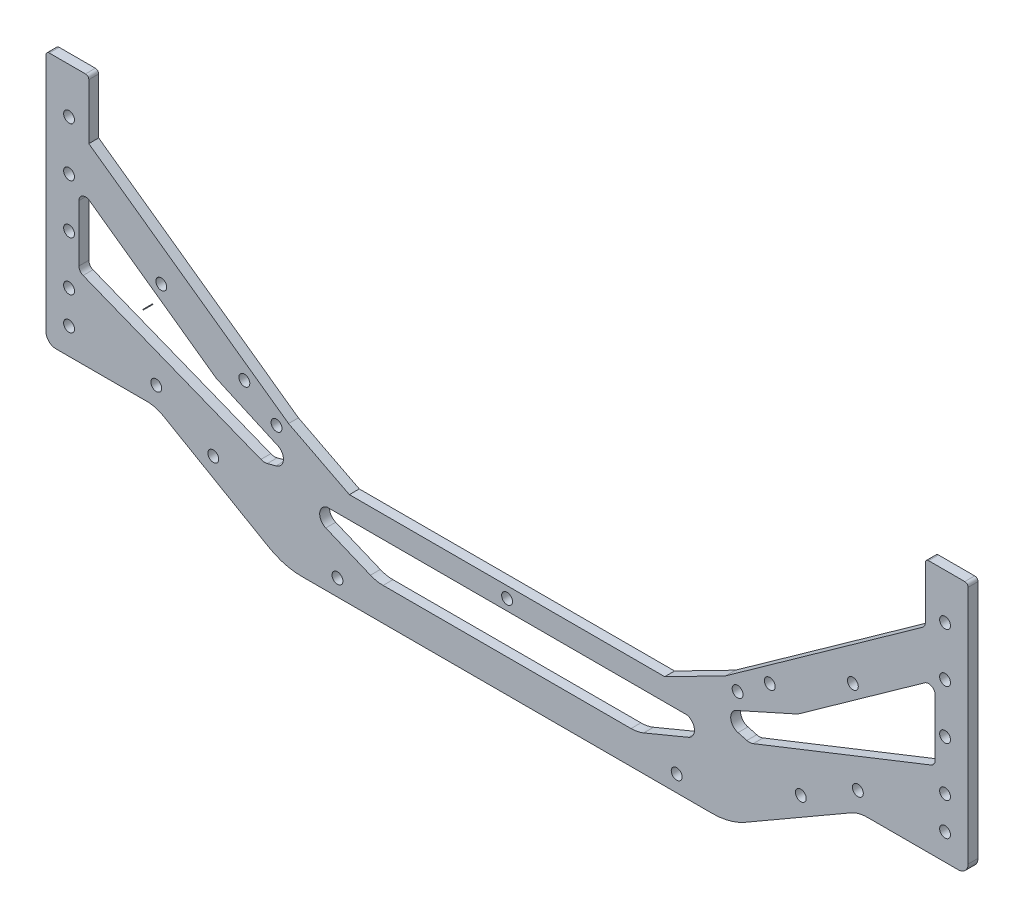
SolidWorks part; units mm, degrees
material "Thornel Mat VMA"
ref_plane "前视基准面" through (0, 0, 0) normal (0, 0, 1) x (1, 0, 0)
ref_plane "上视基准面" through (0, 0, 0) normal (0, 1, 0) x (1, 0, 0)
ref_plane "右视基准面" through (0, 0, 0) normal (1, 0, 0) x (0, 0, -1)
sketch "草图1" plane through (0, 0, 0) normal (0, 0, 1) x (1, 0, 0)
  line L0 (0, 0) -> (53, 0) construction
  line L1 (26.5, 0) -> (26.5, 36.4986) construction
  line L2 (91.5, 5) -> (-38.5, 5)
  line L3 (-38.5, 5) -> (-103.5, 42.5278)
  line L4 (-103.5, 42.5278) -> (-108.5, 33.8675)
  line L5 (-108.5, 33.8675) -> (-41.1795, -5)
  line L6 (-41.1795, -5) -> (94.1795, -5)
  line L7 (161.5, 33.8675) -> (94.1795, -5)
  line L8 (156.5, 42.5278) -> (161.5, 33.8675)
  line L9 (91.5, 5) -> (156.5, 42.5278)
  circle A0 centre (0, 0) radius 1.65
  circle A1 centre (53, 0) radius 1.65
  circle A2 centre (53, 0) radius 1.65
  point P17 (26.5, -5)
  point P20 (26.5, 5)
  dimension "D1" = 3.3
  dimension "D2" = 3.3
  dimension "D3" = 53
  dimension "D7" = 5
  dimension "D4" = 65
  dimension "D5" = 65
  dimension "D6" = 10
  dimension "D8" = 10
  dimension "D9" = 150
extrude "凸台-拉伸1" add sketch "草图1" along normal blind 3 contours L9 L2 L3 L4 L5 L6 L7 L8 A1 A0
fillet "圆角1" radius 20 4 edges at (94.1795, -5, 1.5) (91.5, 5, 1.5) (-41.1795, -5, 1.5) (-38.5, 5, 1.5)
sketch "草图2" plane through (0, 0, 3) normal (0, 0, 1) x (1, 0, 0)
  line L0 (-99.1343, 34.2337) -> (-40.4103, 0.3294) construction
  line L1 (-108.5, 33.8675) -> (-45.8205, -2.3205) construction
  line L2 (-43.141, 7.6795) -> (-103.5, 42.5278) construction
  line L3 (-103.5, 42.5278) -> (-108.5, 33.8675) construction
  line L4 (26.5, 5) -> (26.5, 36.9406) construction
  line L5 (86.141, 5) -> (-33.141, 5) construction
  circle A1 centre (-62.6987, 13.1976) radius 1.65
  circle A2 centre (-80.0192, 23.1976) radius 1.65
  circle A3 centre (133.0192, 23.1976) radius 1.65
  circle A4 centre (115.6987, 13.1976) radius 1.65
  circle A6 centre (-25, 0) radius 1.65
  circle A7 centre (0, 0) radius 1.65 construction
  circle A8 centre (78, 0) radius 1.65
  dimension "D2" = 3.3
  dimension "D3" = 3.3
  dimension "D4" = 3.3
  dimension "D5" = 30
  dimension "D6" = 20
  dimension "D7" = 25
  dimension "D1" = 5
extrude "切除-拉伸1" cut sketch "草图2" against normal blind 10
sketch "草图3" plane through (0, 0, 3) normal (0, 0, 1) x (1, 0, 0)
  line L0 (-103.5, 42.5278) -> (-13.141, 5)
  line L1 (-43.141, 7.6795) -> (-103.5, 42.5278) construction
  line L2 (86.141, 5) -> (-33.141, 5) construction
  line L3 (-13.141, 5) -> (-33.141, 5)
  line L4 (-43.141, 7.6795) -> (-103.5, 42.5278)
  line L5 (26.5, 5) -> (26.5, 26.1465) construction
  line L6 (156.5, 42.5278) -> (66.141, 5)
  line L7 (96.141, 7.6795) -> (156.5, 42.5278)
  line L8 (66.141, 5) -> (86.141, 5)
  arc A0 (-43.141, 7.6795) -> (-33.141, 5) centre (-33.141, 25) ccw construction
  arc A1 (-43.141, 7.6795) -> (-33.141, 5) centre (-33.141, 25) ccw
  arc A2 (96.141, 7.6795) -> (86.141, 5) centre (86.141, 25) cw
  dimension "D1" = 20
extrude "凸台-拉伸2" add sketch "草图3" against normal up to vertex (3 mm away)
fillet "圆角2" radius 10 2 edges at (66.141, 5, 1.5) (-13.141, 5, 1.5)
sketch "草图4" plane through (0, 0, 3) normal (0, 0, 1) x (1, 0, 0)
  line L0 (-103.5, 42.5278) -> (-108.5, 33.8675)
  line L1 (-108.5, 33.8675) -> (-80.1987, 17.5278)
  line L2 (-108.5, 33.8675) -> (-45.8205, -2.3205) construction
  line L3 (-80.1987, 17.5278) -> (-113.5, 17.5278)
  line L4 (-113.5, 17.5278) -> (-113.5, 42.5278)
  line L5 (-113.5, 42.5278) -> (-103.5, 42.5278)
  line L6 (26.5, 5) -> (26.5, 66.9816) construction
  line L7 (64.147, 5) -> (-11.147, 5) construction
  line L8 (166.5, 17.5278) -> (166.5, 42.5278)
  line L9 (133.1987, 17.5278) -> (166.5, 17.5278)
  line L10 (161.5, 33.8675) -> (133.1987, 17.5278)
  line L11 (156.5, 42.5278) -> (161.5, 33.8675)
  line L12 (166.5, 42.5278) -> (156.5, 42.5278)
  dimension "D1" = 25
  dimension "D2" = 10
extrude "凸台-拉伸3" add sketch "草图4" against normal up to surface (3 mm away) up to face at (26.5, 13.1653, 0)
fillet "圆角3" radius 10 2 edges at (133.1987, 17.5278, 1.5) (-80.1987, 17.5278, 1.5)
fillet "圆角4" radius 3 4 edges at (166.5, 42.5278, 1.5) (166.5, 17.5278, 1.5) (-113.5, 42.5278, 1.5) (-113.5, 17.5278, 1.5)
sketch "草图6" plane through (0, 0, 3) normal (0, 0, 1) x (1, 0, 0)
  line L0 (26.5, 5) -> (26.5, 46.6071) construction
  line L1 (64.147, 5) -> (-11.147, 5) construction
  line L2 (-103.5, 42.5278) -> (-110.5, 42.5278) construction
  line L3 (-113.5, 39.5278) -> (-113.5, 20.5278) construction
  circle A0 centre (-106.5, 35.5278) radius 1.65
  circle A1 centre (-106.5, 25.5278) radius 1.65
  circle A2 centre (159.5, 25.5278) radius 1.65
  circle A3 centre (159.5, 35.5278) radius 1.65
  dimension "D1" = 3.3
  dimension "D2" = 3.3
  dimension "D3" = 7
  dimension "D4" = 10
  dimension "D5" = 7
extrude "切除-拉伸2" cut sketch "草图6" against normal blind 5
sketch "草图7" plane through (0, 0, 3) normal (0, 0, 1) x (1, 0, 0)
  line L0 (-47.3074, 19.1899) -> (-13.5, 28.2486)
  line L1 (-14.9825, 5.7648) -> (-103.5, 42.5278) construction
  line L2 (-13.5, 28.2486) -> (26.5, 28.2486)
  line L3 (26.5, 5) -> (26.5, 100.835) construction
  line L4 (64.147, 5) -> (-11.147, 5) construction
  line L5 (-45.4957, 12.4285) -> (-12.5784, 21.2486)
  line L6 (-12.5784, 21.2486) -> (26.5, 21.2486)
  line L7 (-47.3074, 19.1899) -> (-45.4957, 12.4285)
  line L8 (65.5784, 21.2486) -> (26.5, 21.2486)
  line L9 (98.4957, 12.4285) -> (65.5784, 21.2486)
  line L10 (66.5, 28.2486) -> (26.5, 28.2486)
  line L11 (100.3074, 19.1899) -> (66.5, 28.2486)
  line L12 (100.3074, 19.1899) -> (98.4957, 12.4285)
  dimension "D1" = 165
  dimension "D2" = 35
  dimension "D3" = 40
  dimension "D4" = 7
extrude "凸台-拉伸4" add sketch "草图7" against normal up to surface (3 mm away) up to face at (161.15, 35.5278, 0)
sketch "草图8" plane through (0, 0, 3) normal (0, 0, 1) x (1, 0, 0)
  line L0 (26.5, 5) -> (26.5, 83.5373) construction
  line L1 (64.147, 5) -> (-11.147, 5) construction
  circle A0 centre (-106.5, 25.5278) radius 1.65 construction
  circle A1 centre (-106.5, 35.5278) radius 1.65 construction
  circle A2 centre (-106.5, 25.5278) radius 1.65
  circle A3 centre (-106.5, 35.5278) radius 1.65
  circle A4 centre (-98.5, 35.5278) radius 1.65
  circle A5 centre (-98.5, 25.5278) radius 1.65
  circle A6 centre (151.5, 25.5278) radius 1.65
  circle A7 centre (151.5, 35.5278) radius 1.65
  circle A8 centre (159.5, 35.5278) radius 1.65
  circle A9 centre (159.5, 25.5278) radius 1.65
  dimension "D1" = 2
extrude "切除-拉伸3" cut sketch "草图8" against normal blind 10
sketch "草图9" plane through (0, 0, 3) normal (0, 0, 1) x (1, 0, 0)
  line L0 (-13.5, 28.2486) -> (-110.9118, 54.35)
  line L1 (-110.9118, 54.35) -> (-113.5, 44.6908)
  line L2 (-113.5, 44.6908) -> (-32.8185, 23.0722)
  line L3 (-13.5, 28.2486) -> (-47.3074, 19.1899) construction
  line L4 (66.5, 28.2486) -> (-13.5, 28.2486) construction
  line L5 (-106.5, 35.5278) -> (-106.5, 52.0247) construction
  line L6 (-32.8185, 23.0722) -> (-13.5, 28.2486)
  line L7 (26.5, 28.2486) -> (26.5, 99.0808) construction
  line L8 (166.5, 44.6908) -> (85.8185, 23.0722)
  line L9 (163.9118, 54.35) -> (166.5, 44.6908)
  line L10 (66.5, 28.2486) -> (163.9118, 54.35)
  line L11 (85.8185, 23.0722) -> (66.5, 28.2486)
  line L12 (-113.5, 39.5278) -> (-113.5, 20.5278) construction
  dimension "D3" = 10
  dimension "D4" = 165
extrude "凸台-拉伸5" add sketch "草图9" against normal up to surface (3 mm away) up to face at (153.15, 25.5278, 0)
fillet "圆角5" radius 3 14 edges at (66.5, 28.2486, 1.5) (-13.5, 28.2486, 1.5) (-32.8185, 23.0722, 1.5) (-47.3074, 19.1899, 1.5) (-36.7011, 14.7849, 1.5) (-12.5784, 21.2486, 1.5) (65.5784, 21.2486, 1.5) (89.7011, 14.7849, 1.5) (100.3074, 19.1899, 1.5) (85.8185, 23.0722, 1.5) (166.5, 44.6908, 1.5) (163.9118, 54.35, 1.5) (-113.5, 44.6908, 1.5) (-110.9118, 54.35, 1.5)
sketch "草图10" plane through (0, 0, 3) normal (0, 0, 1) x (1, 0, 0)
  line L0 (174.5, 103.4145) -> (174.5, 73.4145) construction
  line L1 (-121.5, 103.4145) -> (-121.5, 73.4145) construction
  line L2 (-108.3577, 67.8631) -> (-113.5, 61.7348)
  line L3 (-113.5, 61.7348) -> (-101.7846, 51.9044)
  line L4 (-13.8815, 28.3508) -> (-108.014, 53.5736) construction
  line L5 (-101.7846, 51.9044) -> (-83.5, 47.005)
  line L6 (-83.5, 47.005) -> (-108.3577, 67.8631)
  line L7 (-113.5, 39.5278) -> (-113.5, 20.5278) construction
  line L8 (26.5, 28.2486) -> (26.5, 127.7041) construction
  line L9 (66.105, 28.2486) -> (-13.105, 28.2486) construction
  line L10 (136.5, 47.005) -> (161.3577, 67.8631)
  line L11 (154.7846, 51.9044) -> (136.5, 47.005)
  line L12 (166.5, 61.7348) -> (154.7846, 51.9044)
  line L13 (161.3577, 67.8631) -> (166.5, 61.7348)
  dimension "D3" = 8
  dimension "D4" = 155
  dimension "D5" = 38
extrude "凸台-拉伸6" add sketch "草图10" against normal up to vertex (3 mm away)
fillet "圆角6" radius 2 8 edges at (161.3577, 67.8631, 1.5) (166.5, 61.7348, 1.5) (154.7846, 51.9044, 1.5) (136.5, 47.005, 1.5) (-83.5, 47.005, 1.5) (-101.7846, 51.9044, 1.5) (-108.3577, 67.8631, 1.5) (-113.5, 61.7348, 1.5)
sketch "草图11" plane through (0, 0, 3) normal (0, 0, 1) x (1, 0, 0)
  line L0 (26.5, 28.2486) -> (26.5, 115.9487) construction
  line L1 (-113.5, 39.5278) -> (-103.5, 39.5278)
  line L2 (-113.5, 39.5278) -> (-113.5, 106.9145)
  line L3 (-113.5, 106.9145) -> (-103.5, 106.9145)
  line L4 (-103.5, 39.5278) -> (-103.5, 106.9145)
  line L5 (66.105, 28.2486) -> (-13.105, 28.2486) construction
  line L6 (156.5, 39.5278) -> (156.5, 106.9145)
  line L7 (166.5, 106.9145) -> (156.5, 106.9145)
  line L8 (166.5, 39.5278) -> (166.5, 106.9145)
  line L9 (166.5, 39.5278) -> (156.5, 39.5278)
  dimension "D2" = 10
extrude "凸台-拉伸7" add sketch "草图11" against normal up to surface (3 mm away) up to face at (108.924, 25.2185, 0)
sketch "草图14" plane through (0, 0, 3) normal (0, 0, 1) x (1, 0, 0)
  line L0 (166.5, 20.5278) -> (166.5, 106.9145) construction
  line L1 (-113.5, 106.9145) -> (166.5, 106.9145)
  line L2 (-113.5, 106.9145) -> (-113.5, 97.32)
  line L3 (-113.5, 97.32) -> (166.5, 97.32)
  line L4 (166.5, 106.9145) -> (166.5, 97.32)
extrude "切除-拉伸6" cut sketch "草图14" against normal blind 30
sketch "草图15" plane through (0, 0, 3) normal (0, 0, 1) x (1, 0, 0)
  line L0 (-48.2493, 19.5811) -> (-113.5, 45.4145)
  line L1 (-113.5, 45.4145) -> (-113.5, 58.9239)
  line L2 (-113.5, 58.9239) -> (-71.8142, 33.5211)
  line L3 (-99.9952, 41.0722) -> (-43.6332, 25.97) construction
  line L4 (-71.8142, 33.5211) -> (-43.6332, 25.97)
  line L5 (-113.5, 97.32) -> (-113.5, 20.5278) construction
  line L6 (-43.6332, 20.1744) -> (-46.3222, 19.4539)
  line L7 (26.5, 28.2486) -> (26.5, 82.7426) construction
  line L8 (66.105, 28.2486) -> (-13.105, 28.2486) construction
  line L9 (124.8142, 33.5211) -> (96.6332, 25.97)
  line L10 (166.5, 58.9239) -> (124.8142, 33.5211)
  line L11 (166.5, 45.4145) -> (166.5, 58.9239)
  line L12 (101.2493, 19.5811) -> (166.5, 45.4145)
  line L13 (96.6332, 20.1744) -> (99.3222, 19.4539)
  arc A0 (-48.2493, 19.5811) -> (-46.3222, 19.4539) centre (-47.0987, 22.3517) ccw construction
  arc A1 (-43.6332, 20.1744) -> (-43.6332, 25.97) centre (-44.4096, 23.0722) ccw construction
  arc A2 (-48.2493, 19.5811) -> (-46.3222, 19.4539) centre (-47.0987, 22.3517) ccw
  arc A3 (-43.6332, 20.1744) -> (-43.6332, 25.97) centre (-44.4096, 23.0722) ccw
  arc A4 (96.6332, 20.1744) -> (96.6332, 25.97) centre (97.4096, 23.0722) cw
  arc A5 (101.2493, 19.5811) -> (99.3222, 19.4539) centre (100.0987, 22.3517) cw
extrude "切除-拉伸7" cut sketch "草图15" against normal blind 10
sketch "草图16" plane through (0, 0, 3) normal (0, 0, 1) x (1, 0, 0)
  line L1 (-13.8815, 28.3508) -> (-83.0717, 46.8903) construction
  line L2 (-48.4766, 37.6206) -> (-84.0799, 40.9549)
  line L3 (-84.0799, 40.9549) -> (-103.5, 62.787)
  line L5 (136.0717, 46.8903) -> (66.8815, 28.3508) construction
  line L6 (101.4766, 37.6206) -> (136.7238, 40.9549)
  line L7 (136.7238, 40.9549) -> (156.5, 62.787)
  line L9 (-103.5, 62.787) -> (-103.5, 65.787)
  line L10 (-103.5, 63.787) -> (-103.5, 97.32) construction
  line L11 (-103.5, 65.787) -> (-48.4766, 37.6206)
  line L12 (101.4766, 37.6206) -> (156.5, 65.787)
  line L14 (156.5, 65.787) -> (156.5, 62.787)
  line L17 (156.5, 97.32) -> (156.5, 63.787) construction
  dimension "D1" = 3
  dimension "D2" = 1
  dimension "D3" = 3
  dimension "D4" = 1
extrude "凸台-拉伸12" add sketch "草图16" against normal up to vertex (3 mm away)
sketch "草图18" plane through (0, 0, 3) normal (0, 0, 1) x (1, 0, 0)
sketch "草图20" plane through (0, 0, 3) normal (0, 0, 1) x (1, 0, 0)
  line L6 (81.1777, 17.0688) -> (-28.1777, 17.0688)
  line L8 (-28.1777, 17.0688) -> (-12.1835, 24.1453)
  line L9 (-12.1835, 24.1453) -> (57.5138, 24.1453)
  line L10 (57.5138, 24.1453) -> (81.1777, 17.0688)
extrude "凸台-拉伸15" add sketch "草图20" against normal up to surface (3 mm away) up to face at (18.4088, 34.2671, 0)
sketch "草图21" plane through (0, 0, 0) normal (0, 0, -1) x (-1, 0, 0)
  line L0 (-101.4766, 37.6206) -> (-74.3777, 23.7486)
  line L1 (-74.3777, 23.7486) -> (21.3777, 23.7486)
  line L2 (21.3777, 23.7486) -> (46.901, 36.814)
  line L3 (48.4766, 37.6206) -> (103.5, 65.787) construction
  line L4 (-156.5, 65.787) -> (-101.4766, 37.6206) construction
  line L6 (13.105, 28.2486) -> (-66.105, 28.2486) construction
  line L7 (-101.4766, 37.6206) -> (46.901, 36.814)
  dimension "D1" = 4.5
extrude "切除-拉伸10" cut sketch "草图21" against normal blind 10
sketch "草图22" plane through (0, 0, 3) normal (0, 0, 1) x (1, 0, 0)
  line L0 (-113.5, 45.4145) -> (-48.2493, 19.5811) construction
  line L1 (-113.5, 58.9239) -> (-103.5, 58.9239)
  line L2 (-113.5, 58.9239) -> (-113.5, 41.4554)
  line L3 (-113.5, 41.4554) -> (-103.5, 41.4554)
  line L4 (-103.5, 58.9239) -> (-103.5, 41.4554)
  line L5 (101.2493, 19.5811) -> (166.5, 45.4145) construction
  line L6 (166.5, 58.9239) -> (156.5, 58.9239)
  line L7 (166.5, 58.9239) -> (166.5, 41.4554)
  line L8 (166.5, 41.4554) -> (156.5, 41.4554)
  line L9 (156.5, 58.9239) -> (156.5, 41.4554)
extrude "凸台-拉伸16" add sketch "草图22" against normal up to surface (3 mm away) up to face at (26.5, 9.7947, 0)
sketch "草图23" plane through (0, 0, 3) normal (0, 0, 1) x (1, 0, 0)
  line L0 (-103.5, 52.83) -> (-43.6332, 25.97)
  line L1 (-43.6332, 25.97) -> (-71.8142, 33.5211)
  line L2 (-71.8142, 33.5211) -> (-103.5, 52.83)
  line L3 (96.6332, 25.97) -> (156.5, 52.83)
  line L4 (156.5, 52.83) -> (124.8142, 33.5211)
  line L5 (124.8142, 33.5211) -> (96.6332, 25.97)
extrude "切除-拉伸11" cut sketch "草图23" against normal blind 10
sketch "草图24" plane through (0, 0, 3) normal (0, 0, 1) x (1, 0, 0)
  line L0 (-46.901, 36.814) -> (-54.0368, 40.4668)
  line L1 (-48.4766, 37.6206) -> (-103.5, 65.787) construction
  line L2 (-54.0368, 40.4668) -> (-39.643, 38.6404)
  line L3 (-39.643, 38.6404) -> (-44.3618, 35.5142)
  line L4 (-46.901, 36.814) -> (-21.3777, 23.7486) construction
  line L5 (-44.3618, 35.5142) -> (-46.901, 36.814)
extrude "切除-拉伸12" cut sketch "草图24" against normal blind 10
sketch "草图25" plane through (0, 0, 3) normal (0, 0, 1) x (1, 0, 0)
  line L1 (-113.5, 97.32) -> (166.5, 97.32)
  line L2 (-113.5, 97.32) -> (-113.5, 94.32)
  line L3 (-113.5, 94.32) -> (166.5, 94.32)
  line L4 (166.5, 97.32) -> (166.5, 94.32)
  line L5 (166.5, 20.5278) -> (166.5, 97.32) construction
  dimension "D1" = 3
  dimension "D2" = 280
extrude "切除-拉伸13" cut sketch "草图25" against normal blind 10
sketch "草图26" plane through (0, 0, 3) normal (0, 0, 1) x (1, 0, 0)
  line L1 (-103.5, 94.32) -> (-100.5, 94.32)
  line L2 (-103.5, 94.32) -> (-103.5, 59.32)
  line L3 (-103.5, 59.32) -> (-100.5, 59.32)
  line L4 (-100.5, 94.32) -> (-100.5, 59.32)
  line L5 (156.5, 94.32) -> (153.5, 94.32)
  line L6 (156.5, 94.32) -> (156.5, 59.32)
  line L7 (156.5, 59.32) -> (153.5, 59.32)
  line L8 (153.5, 94.32) -> (153.5, 59.32)
  dimension "D1" = 35
  dimension "D2" = 3
  dimension "D3" = 35
  dimension "D4" = 3
extrude "凸台-拉伸17" add sketch "草图26" against normal up to surface (3 mm away) up to face at (26.5, 34.1676, 0)
sketch "草图27" plane through (0, 0, 3) normal (0, 0, 1) x (1, 0, 0)
  line L0 (-106.5, 35.5278) -> (-106.5, 80.5278) construction
  line L1 (159.5, 35.5278) -> (159.5, 80.5278) construction
  circle A0 centre (-106.5, 65.5278) radius 1.65
  circle A1 centre (-106.5, 80.5278) radius 1.65
  circle A2 centre (-106.5, 35.5278) radius 1.65 construction
  circle A3 centre (159.5, 65.5278) radius 1.65
  circle A4 centre (159.5, 80.5278) radius 1.65
  circle A5 centre (159.5, 35.5278) radius 1.65 construction
  circle A6 centre (-106.5, 50.5278) radius 1.65
  circle A7 centre (159.5, 50.5278) radius 1.65
  dimension "D1" = 3.3
  dimension "D2" = 3.3
  dimension "D3" = 30
  dimension "D4" = 15
  dimension "D5" = 3.3
  dimension "D6" = 3.3
  dimension "D8" = 15
  dimension "D9" = 3.3
  dimension "D10" = 3.3
  dimension "D11" = 15
  dimension "D12" = 15
  dimension "D7" = 30
extrude "切除-拉伸14" cut sketch "草图27" against normal blind 10
fillet "圆角7" radius 1 4 edges at (166.5, 94.32, 1.5) (153.5, 94.32, 1.5) (-113.5, 94.32, 1.5) (-100.5, 94.32, 1.5)
sketch "草图28" plane through (0, 0, 3) normal (0, 0, 1) x (1, 0, 0)
  circle A0 centre (-98.5, 25.5278) radius 1.65 construction
  circle A1 centre (-98.5, 35.5278) radius 1.65 construction
  circle A2 centre (151.5, 25.5278) radius 1.65 construction
  circle A3 centre (151.5, 35.5278) radius 1.65 construction
  circle A4 centre (-98.5, 25.5278) radius 1.65
  circle A5 centre (-98.5, 35.5278) radius 1.65
  circle A6 centre (151.5, 25.5278) radius 1.65
  circle A7 centre (151.5, 35.5278) radius 1.65
extrude "凸台-拉伸18" add sketch "草图28" against normal up to surface (3 mm away) up to face at (-104.85, 50.5278, 0)
sketch "草图29" plane through (0, 0, 3) normal (0, 0, 1) x (1, 0, 0)
  line L0 (-100.5, 82.608) -> (-27.3401, 23.0168)
  line L1 (-100.5, 64.2513) -> (-100.5, 93.32) construction
  line L3 (-43.6332, 25.97) -> (-103.5, 52.83) construction
  line L4 (-43.6332, 25.97) -> (-100.5, 72.29)
  line L5 (-100.5, 82.608) -> (-100.5, 72.29)
  line L6 (-43.6332, 25.97) -> (-27.3401, 23.0168)
  dimension "D1" = 15
  dimension "D2" = 8
  dimension "D3" = 8
extrude "凸台-拉伸19" add sketch "草图29" against normal up to surface (3 mm away) up to face at (-104.85, 50.5278, 0)
sketch "草图30" plane through (0, 0, 3) normal (0, 0, 1) x (1, 0, 0)
  line L0 (-100.5, 72.29) -> (-100.5, 64.2513)
  line L1 (-100.5, 64.2513) -> (-73.9377, 50.6541)
  line L2 (-73.9377, 50.6541) -> (-100.5, 72.29)
extrude "凸台-拉伸20" add sketch "草图30" against normal up to surface (3 mm away) up to face at (23.8463, 44.2379, 0)
sketch "草图31" plane through (0, 0, 3) normal (0, 0, 1) x (1, 0, 0)
  line L0 (-103.5, 52.83) -> (-103.5, 60.603)
  line L1 (-103.5, 60.603) -> (-53.1944, 23.244)
  line L3 (-103.5, 41.4554) -> (-48.2493, 19.5811) construction
  line L4 (-100.5, 82.608) -> (-100.5, 78.2472)
  line L5 (-100.5, 78.2472) -> (-39.8437, 33.2014)
  line L6 (-39.8437, 33.2014) -> (-100.5, 82.608)
  line L7 (-103.5, 52.83) -> (-53.1944, 23.244)
  dimension "D1" = 15
extrude "切除-拉伸15" cut sketch "草图31" against normal through all
sketch "草图32" plane through (0, 0, 3) normal (0, 0, 1) x (1, 0, 0)
  line L0 (-103.5, 60.603) -> (-103.5, 63.877)
  line L1 (-103.5, 63.877) -> (-61.7827, 34.113)
  line L2 (-61.7827, 34.113) -> (-77.0594, 40.9671)
  line L3 (-77.0594, 40.9671) -> (-103.5, 60.603)
  line L4 (-103.5, 41.4554) -> (-103.5, 60.603) construction
  line L5 (-100.5, 78.2472) -> (-100.5, 76.4777)
  line L6 (-100.5, 76.4777) -> (-39.8437, 33.2014)
  line L7 (-39.8437, 33.2014) -> (-100.5, 78.2472)
  dimension "D1" = 12
extrude "切除-拉伸16" cut sketch "草图32" against normal through all
ref_plane "基准面1" through (26.5, 0, 0) normal (-1, 0, 0) x (0, 0, 1)
mirror "镜向1" about plane through (26.5, 0, 0) normal (-1, 0, 0) of "凸台-拉伸19", "切除-拉伸16", "凸台-拉伸20", "切除-拉伸15"
sketch "草图33" plane through (0, 0, 3) normal (0, 0, 1) x (1, 0, 0)
  line L0 (-106.5, 50.5278) -> (-78.5, 50.5278) construction
  line L1 (26.5, -5) -> (26.5, 127.4192) construction
  line L2 (-35.8205, -5) -> (88.8205, -5) construction
  line L3 (26.5, 1.65) -> (26.5, -1.65) construction
  circle A0 centre (-78.5, 50.5278) radius 1.65
  circle A1 centre (-106.5, 50.5278) radius 1.65 construction
  circle A2 centre (131.5, 50.5278) radius 1.65
  dimension "D1" = 3.3
  dimension "D2" = 28
extrude "切除-拉伸17" cut sketch "草图33" against normal through all
fillet "圆角8" radius 2 7 edges at (-61.7827, 34.113, 1.5) (-103.5, 41.4554, 1.5) (-103.5, 63.877, 1.5) (114.7827, 34.113, 1.5) (153.5, 76.4777, 1.5) (156.5, 41.4554, 1.5) (156.5, 63.877, 1.5)
sketch "草图34" plane through (0, 0, 3) normal (0, 0, 1) x (1, 0, 0)
  circle A0 centre (0, 0) radius 1.65
  circle A1 centre (53, 0) radius 1.65
extrude "凸台-拉伸21" add sketch "草图34" against normal up to surface (3 mm away) up to face at (-76.85, 50.5278, 0)
sketch "草图35" plane through (0, 0, 0) normal (0, 0, -1) x (-1, 0, 0)
  line L0 (-106.2686, 37.8659) -> (-96.5, 30.8963) construction
  line L1 (-26.5, 23.7486) -> (-26.5, 89.3297) construction
  line L2 (-74.3777, 23.7486) -> (21.3777, 23.7486) construction
  line L3 (-152.6616, 75.8795) -> (-92.8437, 33.2014) construction
  line L4 (53.2686, 37.8659) -> (43.5, 30.8963) construction
  circle A0 centre (-106.2686, 37.8659) radius 1.65
  circle A1 centre (-96.5, 30.8963) radius 1.65
  circle A2 centre (43.5, 30.8963) radius 1.65
  circle A3 centre (53.2686, 37.8659) radius 1.65
  dimension "D4" = 3.3
  dimension "D5" = 3.3
  dimension "D1" = 12
  dimension "D2" = 70
  dimension "D3" = 4
extrude "切除-拉伸18" cut sketch "草图35" against normal blind 10
sketch "草图36" plane through (0, 0, 0) normal (0, 0, -1) x (-1, 0, 0)
  line L0 (-74.3777, 23.7486) -> (21.3777, 23.7486) construction
  line L1 (-81.1777, 17.0688) -> (28.1777, 17.0688) construction
  circle A0 centre (-26.5, 20.3688) radius 1.65
  point P5 (-26.5, 23.7486)
  dimension "D1" = 3.3
  dimension "D2" = 3.3
extrude "切除-拉伸19" cut sketch "草图36" against normal blind 10
